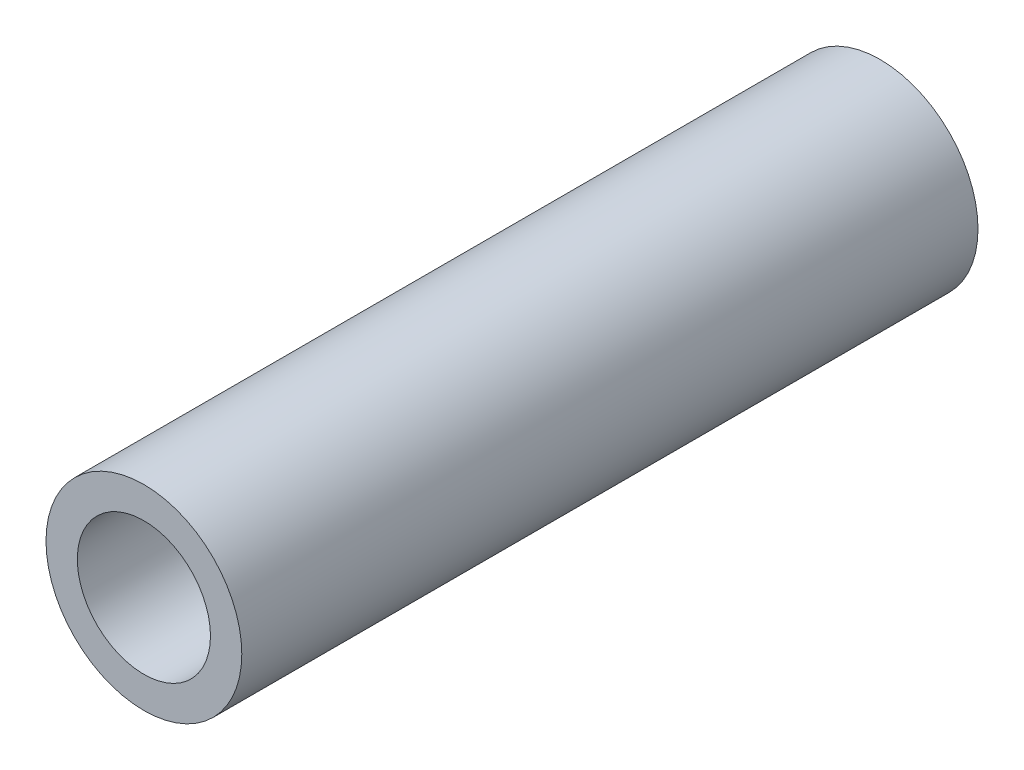
SolidWorks part; units mm, degrees
ref_plane "Front Plane" through (0, 0, 0) normal (1, 0, 0) x (0, 1, 0)
ref_plane "Top Plane" through (0, 0, 0) normal (0, 0, 1) x (0, 1, 0)
ref_plane "Right Plane" through (0, 0, 0) normal (0, 1, 0) x (-1, 0, 0)
sketch "Sketch1" plane through (0, 0, 0) normal (0, 0, 1) x (0, 1, 0)
  circle A0 centre (0, 0) radius 2.5
  dimension "D1" = 5
extrude "Boss-Extrude1" add sketch "Sketch1" along normal blind 18.8
sketch "Sketch2" plane through (0, 0, 18.8) normal (0, 0, 1) x (1, 0, 0)
  circle A0 centre (0, 0) radius 1.7
  dimension "D1" = 3.4
extrude "Cut-Extrude1" cut sketch "Sketch2" against normal through all both and the other way through all
